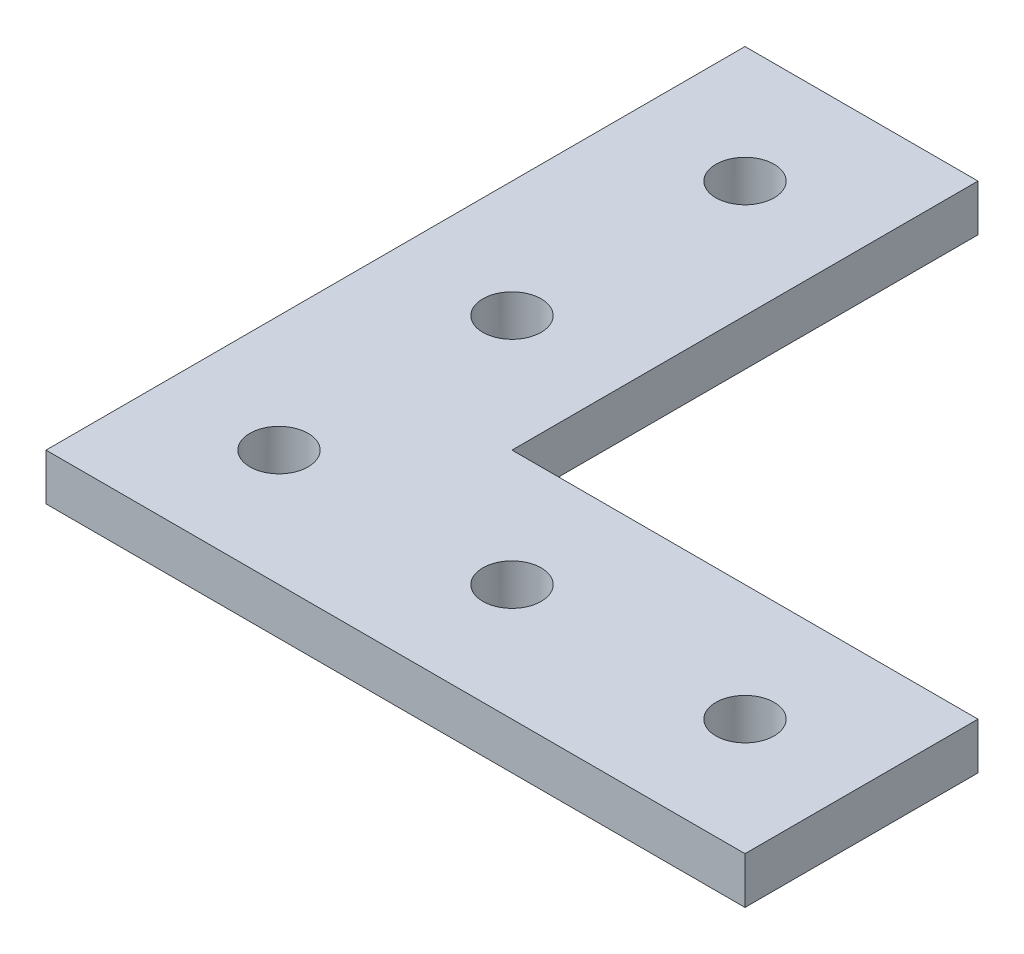
SolidWorks part; units mm, degrees
ref_plane "Front Plane" through (0, 0, 0) normal (0, 0, 1) x (1, 0, 0)
ref_plane "Top Plane" through (0, 0, 0) normal (0, 1, 0) x (1, 0, 0)
ref_plane "Right Plane" through (0, 0, 0) normal (1, 0, 0) x (0, 0, -1)
sketch "Sketch1" plane through (0, 0, 0) normal (0, 1, 0) x (1, 0, 0)
  line L0 (0, 0) -> (0, 76.2)
  line L1 (0, 76.2) -> (25.4, 76.2)
  line L2 (25.4, 76.2) -> (25.4, 25.4)
  line L3 (25.4, 25.4) -> (76.2, 25.4)
  line L4 (76.2, 25.4) -> (76.2, 0)
  line L5 (76.2, 0) -> (0, 0)
  dimension "D1" = 76.2
  dimension "D2" = 76.2
  dimension "D3" = 25.4
  dimension "D4" = 25.4
extrude "Boss-Extrude1" add sketch "Sketch1" along normal blind 5.08
sketch "Sketch2" plane through (0, 5.08, 0) normal (0, 1, 0) x (1, 0, 0)
  line L0 (12.7, 63.5) -> (12.7, 12.7)
  line L1 (12.7, 12.7) -> (63.5, 12.7)
  line L2 (25.4, 76.2) -> (0, 76.2) construction
  line L3 (0, 0) -> (76.2, 0) construction
  line L4 (0, 76.2) -> (0, 0) construction
  line L5 (76.2, 0) -> (76.2, 25.4) construction
  point P11 (38.1, 12.7)
  point P12 (12.7, 63.5)
  point P13 (12.7, 12.7)
  point P14 (63.5, 12.7)
  point P15 (12.7, 38.1)
  dimension "D1" = 12.7
  dimension "D2" = 12.7
  dimension "D3" = 12.7
  dimension "D4" = 12.7
hole_wizard "1/4 (0.25) Diameter Hole1" positions "Sketch3" profile "Sketch4" hole size "1/4" standard "ANSI Inch"
sketch "Sketch3" plane through (0, 5.08, 0) normal (0, 1, 0) x (1, 0, 0)
  point P0 (12.7, 63.5)
  point P3 (12.7, 38.1)
  point P6 (12.7, 12.7)
  point P9 (38.1, 12.7)
  point P12 (63.5, 12.7)
sketch "Sketch4" plane through (12.7, 5.08, -63.5) normal (1, 0, 0) x (0, 0, 1)
  line L0 (0, 0) -> (0, 27.3077)
  line L1 (0, 27.3077) -> (3.175, 25.4)
  line L2 (3.175, 25.4) -> (3.175, 0)
  line L5 (3.175, 0) -> (0, 0)
  line L10 (0, 27.3077) -> (-3.175, 25.4) construction
  line L11 (0, -6.35) -> (0, 107.95) construction
  dimension "Hole Dia." = 6.35
  dimension "Hole Depth" = 25.4
  dimension "Drill Angle" = 118
